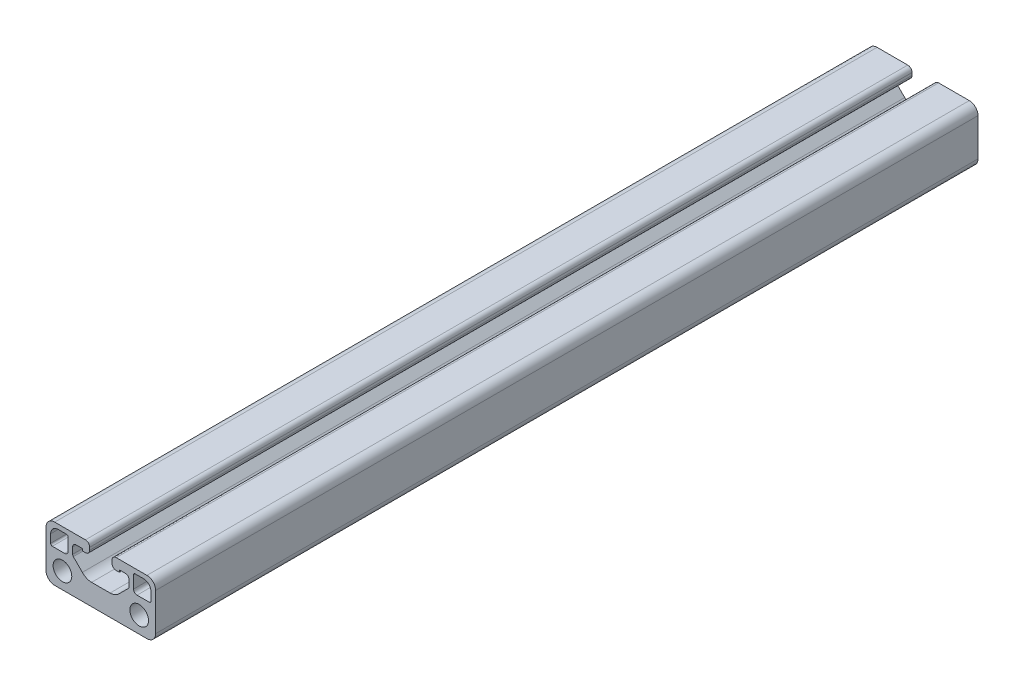
SolidWorks part; units mm, degrees
other "DetailItem1"
material "6105-T5 Aluminum"
ref_plane "Front Plane" through (0, 0, 0) normal (0, 0, 1) x (1, 0, 0)
ref_plane "Top Plane" through (0, 0, 0) normal (0, 1, 0) x (1, 0, 0)
ref_plane "Right Plane" through (0, 0, 0) normal (1, 0, 0) x (0, 0, -1)
sketch "Sketch1" plane through (0, 0, 0) normal (0, 0, 1) x (1, 0, 0)
  line L0 (14, 1.3552) -> (14, -9.1199) construction
  line L1 (-14, 0.8534) -> (-14, -9.1199) construction
  line L2 (-18.7822, -4) -> (18.324, -4) construction
  line L30 (-13.2123, 1.9392) -> (-17.6889, 1.9392)
  line L31 (-18.3171, 2.5742) -> (-18.3171, 5.5656)
  line L32 (-15.4934, 8.3296) -> (-12.5019, 8.3296)
  line L33 (-11.9423, 7.6857) -> (-11.9423, 3.2092)
  line L34 (18.324, 5.5037) -> (18.324, 2.5123)
  line L35 (12.5686, 8.3275) -> (15.5601, 8.3275)
  line L36 (11.9404, 3.2159) -> (11.9404, 7.6925)
  line L37 (17.687, 1.9459) -> (13.2104, 1.9459)
  line L38 (-20, 6.825) -> (-20, -6.825)
  line L39 (-16.825, -10) -> (16.825, -10)
  line L40 (20, -6.825) -> (20, 6.825)
  line L41 (16.825, 10) -> (13.0177, 10)
  line L42 (13.0177, 10) -> (5.6244, 10)
  line L43 (4.06, 8.4356) -> (4.06, 7.5148)
  line L44 (5.6348, 5.94) -> (6.7718, 5.94)
  line L45 (6.7718, 5.94) -> (6.7718, 6.7089)
  line L46 (6.7718, 6.7089) -> (9.0158, 6.7089)
  line L47 (10.285, 5.3946) -> (10.285, 3.0962)
  line L48 (10.1069, 2.5504) -> (6.7378, -0.8187)
  line L49 (3.3792, -2.3) -> (-3.3792, -2.3)
  line L50 (-6.7378, -0.8187) -> (-10.0246, 2.4681)
  line L51 (-10.285, 3.0967) -> (-10.285, 5.3946)
  line L52 (-9.0158, 6.7089) -> (-6.7718, 6.7089)
  line L53 (-6.7718, 6.7089) -> (-6.7718, 5.94)
  line L54 (-6.7718, 5.94) -> (-5.6348, 5.94)
  line L55 (-4.06, 7.5148) -> (-4.06, 8.4356)
  line L56 (-5.6244, 10) -> (-13.0173, 10)
  line L57 (-13.0173, 10) -> (-16.825, 10)
  line L58 (0, -10) -> (0, 0) construction
  line L59 (-20, 0) -> (20, 0) construction
  arc A24 (-18.3171, 2.5742) -> (-17.6889, 1.9392) centre (-17.6821, 2.5742) ccw
  arc A25 (-15.4934, 8.3296) -> (-18.3171, 5.5656) centre (-15.5233, 5.5357) ccw
  arc A26 (-11.9423, 7.6857) -> (-12.5019, 8.3296) centre (-12.5772, 7.6991) ccw
  arc A27 (-13.2123, 1.9392) -> (-11.9423, 3.2092) centre (-13.2123, 3.2092) ccw
  circle A28 centre (-14, -4) radius 3.4036
  circle A29 centre (14, -4) radius 3.4036
  arc A30 (-20, -6.825) -> (-16.825, -10) centre (-16.825, -6.825) ccw
  arc A31 (16.825, -10) -> (20, -6.825) centre (16.825, -6.825) ccw
  arc A32 (20, 6.825) -> (16.825, 10) centre (16.825, 6.825) ccw
  arc A33 (5.6244, 10) -> (4.06, 8.4356) centre (5.6244, 8.4356) ccw
  arc A34 (4.06, 7.5148) -> (5.6348, 5.94) centre (5.6348, 7.5148) ccw
  arc A35 (10.285, 5.3946) -> (9.0158, 6.7089) centre (9.0158, 5.4389) ccw
  arc A36 (10.1069, 2.5504) -> (10.285, 3.0962) centre (9.3961, 3.0842) ccw
  arc A37 (3.3792, -2.3) -> (6.7378, -0.8187) centre (3.2907, 2.449) ccw
  arc A38 (-6.7378, -0.8187) -> (-3.3792, -2.3) centre (-3.2907, 2.449) ccw
  arc A39 (-10.285, 3.0967) -> (-10.0246, 2.4681) centre (-9.396, 3.0967) ccw
  arc A40 (-9.0158, 6.7089) -> (-10.285, 5.3946) centre (-9.0158, 5.4389) ccw
  arc A41 (-5.6348, 5.94) -> (-4.06, 7.5148) centre (-5.6348, 7.5148) ccw
  arc A42 (-4.06, 8.4356) -> (-5.6244, 10) centre (-5.6244, 8.4356) ccw
  arc A43 (-16.825, 10) -> (-20, 6.825) centre (-16.825, 6.825) ccw
  arc A44 (17.687, 1.9459) -> (18.324, 2.5123) centre (17.6928, 2.5809) ccw
  arc A45 (18.324, 5.5037) -> (15.5601, 8.3275) centre (15.5302, 5.5336) ccw
  arc A46 (12.5686, 8.3275) -> (11.9404, 7.6925) centre (12.5754, 7.6925) ccw
  arc A47 (11.9404, 3.2159) -> (13.2104, 1.9459) centre (13.2104, 3.2159) ccw
  dimension "D1" = 40
  dimension "D2" = 28
  dimension "D3" = 20
  dimension "D4" = 6
  dimension "D5" = 20.57
  dimension "D6" = 8.12
  dimension "D7" = 4.06
  dimension "D8" = 12.3
extrude "Extrude1" add sketch "Sketch1" against normal blind 300
